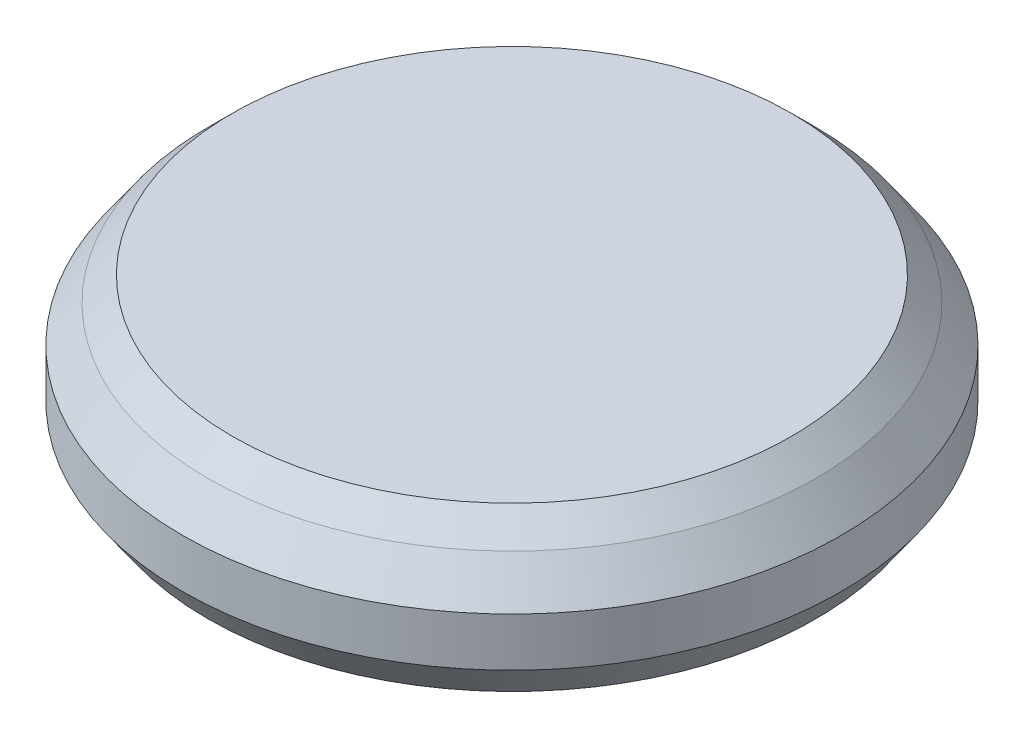
SolidWorks part; units mm, degrees
ref_plane "Alzado" through (0, 0, 0) normal (0, 0, 1) x (1, 0, 0)
ref_plane "Planta" through (0, 0, 0) normal (0, 1, 0) x (1, 0, 0)
ref_plane "Vista lateral" through (0, 0, 0) normal (1, 0, 0) x (0, 0, -1)
sketch "Croquis1" plane through (0, 0, 0) normal (0, 1, 0) x (1, 0, 0)
  circle A0 centre (0, 0) radius 25
  dimension "D1" = 50
extrude "Saliente-Extruir1" add sketch "Croquis1" along normal blind 3 draft 35 draft outward yes
sketch "Croquis2" plane through (0, 3, 0) normal (0, 1, 0) x (1, 0, 0)
  circle A0 centre (0, 0) radius 27.1006
  circle A1 centre (0, 0) radius 27.1006 construction
extrude "Saliente-Extruir2" add sketch "Croquis2" along normal blind 4
sketch "Croquis3" plane through (0, 7, 0) normal (0, 1, 0) x (1, 0, 0)
  circle A0 centre (0, 0) radius 27.1006
  circle A1 centre (0, 0) radius 27.1006 construction
extrude "Saliente-Extruir3" add sketch "Croquis3" along normal blind 3 draft 35
sketch "Croquis4" plane through (0, 10, 0) normal (0, 1, 0) x (1, 0, 0)
  circle A0 centre (0, 0) radius 25
  circle A1 centre (0, 0) radius 25 construction
extrude "Saliente-Extruir4" add sketch "Croquis4" along normal blind 2 draft 45 separate body
